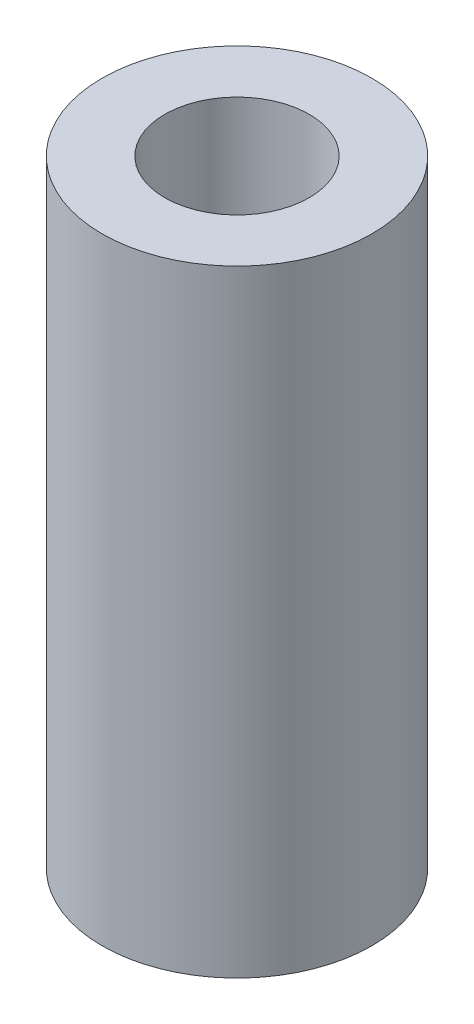
SolidWorks part; units mm, degrees
ref_plane "Front" through (0, 0, 0) normal (0, 0, 1) x (1, 0, 0)
ref_plane "Top" through (0, 0, 0) normal (0, 1, 0) x (1, 0, 0)
ref_plane "Right" through (0, 0, 0) normal (1, 0, 0) x (0, 0, -1)
sketch "Croquis1" plane through (0, 0, 0) normal (0, 1, 0) x (1, 0, 0)
  circle A0 centre (0, 0) radius 3.5
  circle A1 centre (0, 0) radius 1.875
  dimension "D1" = 7
  dimension "D2" = 3.75
extrude "Saliente-Extruir1" add sketch "Croquis1" along normal blind 16
